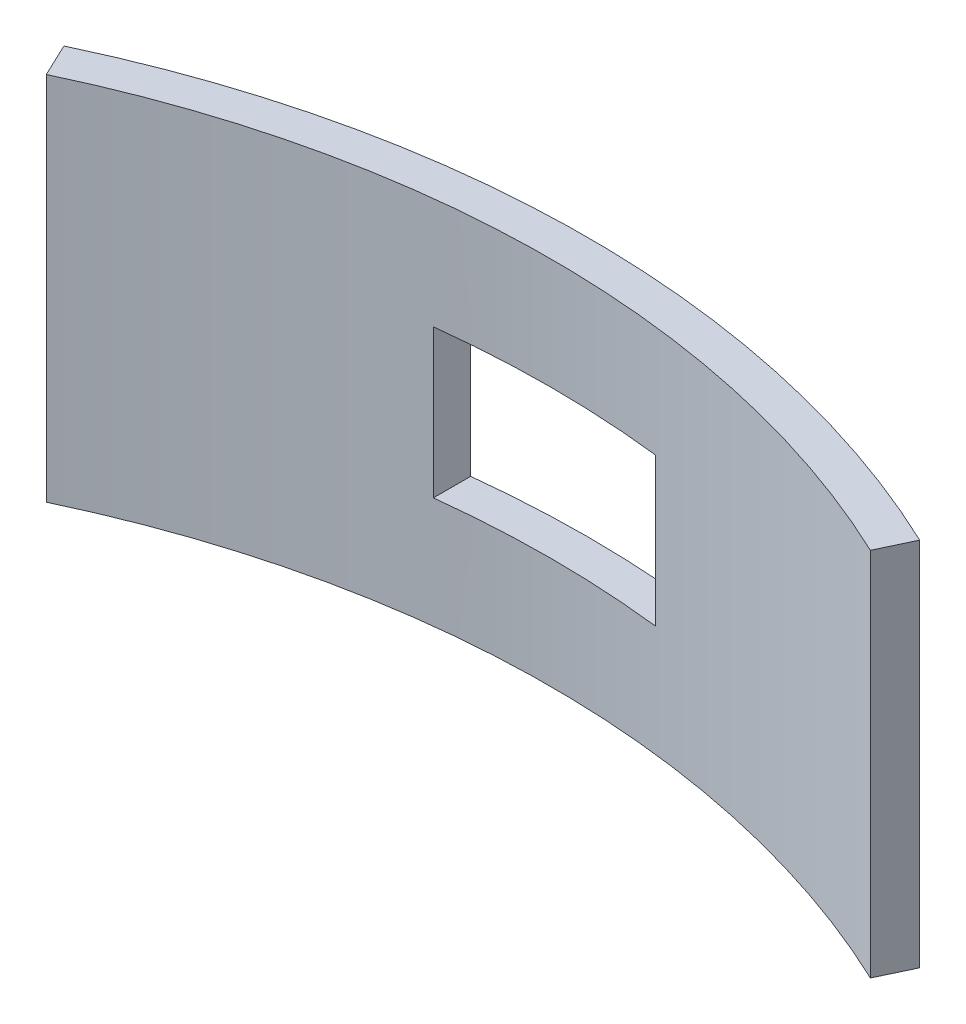
SolidWorks part; units mm, degrees
ref_plane "Front Plane" through (0, 0, 0) normal (0, 0, 1) x (1, 0, 0)
ref_plane "Top Plane" through (0, 0, 0) normal (0, 1, 0) x (1, 0, 0)
ref_plane "Right Plane" through (0, 0, 0) normal (1, 0, 0) x (0, 0, -1)
sketch "Sketch1" plane through (0, 0, 0) normal (0, 1, 0) x (1, 0, 0)
  line L0 (-29.3425, 61.9858) -> (-28.2557, 59.69)
  line L1 (28.2557, 59.69) -> (29.3425, 61.9858)
  arc A0 (-29.3425, 61.9858) -> (29.3425, 61.9858) centre (0, 0) cw
  arc A1 (-28.2557, 59.69) -> (28.2557, 59.69) centre (0, 0) cw
  point P7 (59.381, 34.3091)
  dimension "D1" = 68.58
  dimension "D3" = 59.69
  dimension "D2" = 2.54
extrude "Boss-Extrude1" add sketch "Sketch1" along normal blind 25.4
sketch "Sketch2" plane through (0, 0, 0) normal (0, 0, 1) x (1, 0, 0)
  line L0 (-28.2557, 12.7) -> (28.2557, 12.7) construction
  line L1 (-7.62, 17.78) -> (7.62, 17.78)
  line L2 (-7.62, 17.78) -> (-7.62, 7.62)
  line L3 (-7.62, 7.62) -> (7.62, 7.62)
  line L4 (7.62, 17.78) -> (7.62, 7.62)
  line L5 (-7.62, 17.78) -> (7.62, 7.62) construction
  line L6 (-7.62, 7.62) -> (7.62, 17.78) construction
  line L7 (-28.2557, 25.4) -> (-28.2557, 0) construction
  line L8 (28.2557, 25.4) -> (28.2557, 0) construction
  point P0 (0, 12.7)
  point P5 (0, 12.7)
  dimension "D1" = 15.24
  dimension "D2" = 10.16
extrude "Cut-Extrude1" cut sketch "Sketch2" against normal blind 144.272
